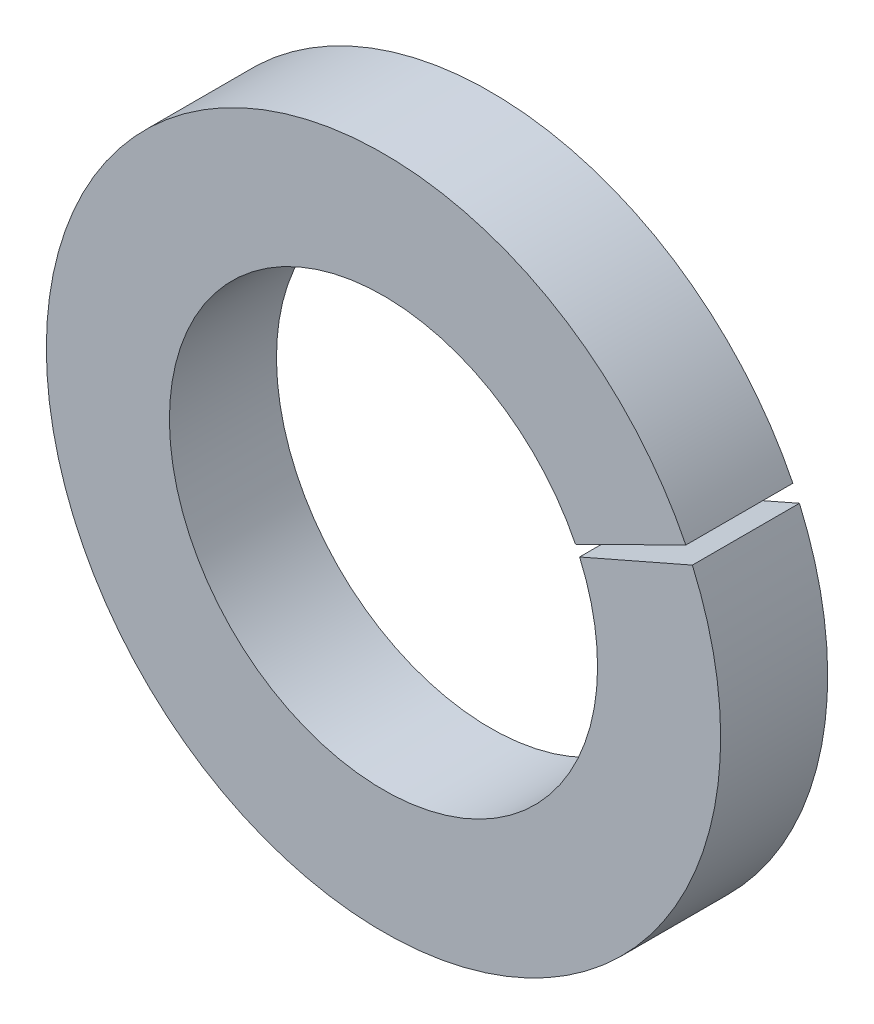
SolidWorks part; units mm, degrees
ref_plane "前视基准面" through (0, 0, 0) normal (0, 0, 1) x (1, 0, 0)
ref_plane "上视基准面" through (0, 0, 0) normal (0, 1, 0) x (1, 0, 0)
ref_plane "右视基准面" through (0, 0, 0) normal (1, 0, 0) x (0, 0, -1)
sketch "草图1" plane through (0, 0, 0) normal (0, 0, 1) x (1, 0, 0)
  circle A0 centre (0, 0) radius 3.15
  circle A1 centre (0, 0) radius 2
  dimension "D1" = 4
  dimension "D2" = 6.3
extrude "凸台-拉伸1" add sketch "草图1" along normal blind 1
sketch "草图2" plane through (0, 0, 1) normal (0, 0, 1) x (1, 0, 0)
  line L0 (0, 0) -> (4.8125, 2.3756)
  line L1 (4.8125, 2.3756) -> (4.8125, 2.1059)
  line L2 (4.8125, 2.1059) -> (0, 0)
extrude "切除-拉伸1" cut sketch "草图2" against normal blind 10
